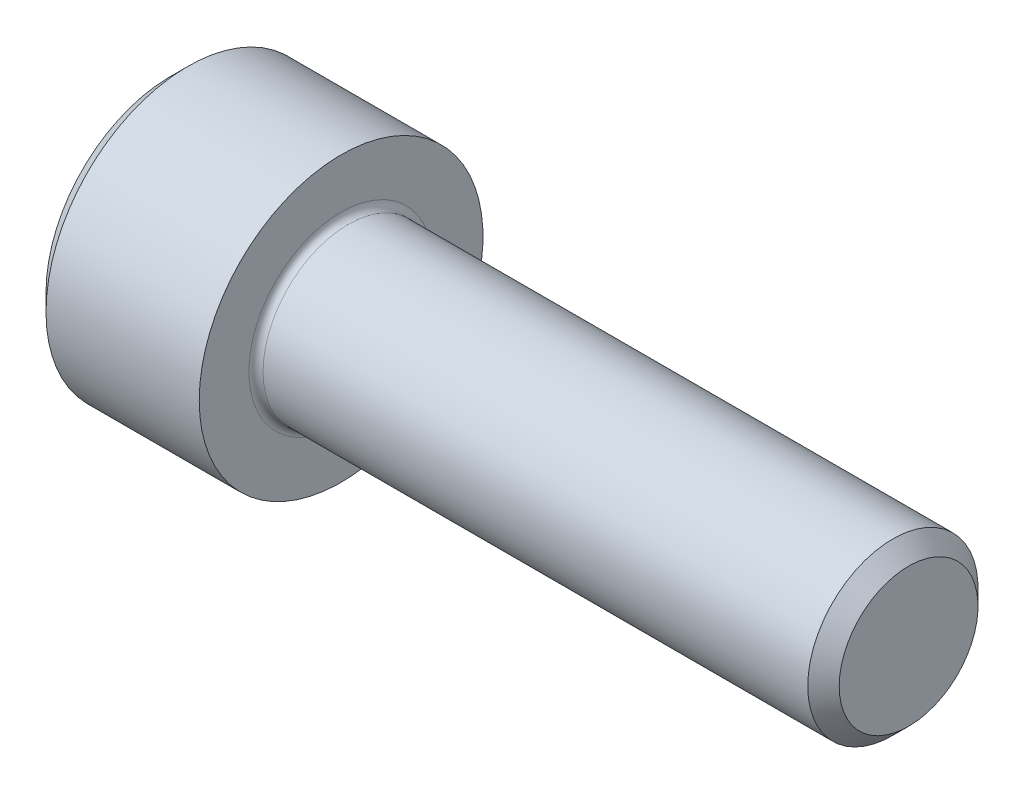
SolidWorks part; units mm, degrees
ref_plane "Plane1" through (0, 0, 0) normal (0, 0, 1) x (1, 0, 0)
ref_plane "Plane2" through (0, 0, 0) normal (0, 1, 0) x (1, 0, 0)
ref_plane "Plane3" through (0, 0, 0) normal (1, 0, 0) x (0, 0, -1)
sketch "BodySke" plane through (0, 0, 0) normal (0, 0, 1) x (1, 0, 0)
  line L0 (0, 0) -> (0, 4.4)
  line L1 (0.6, 5) -> (6, 5)
  line L2 (6, 5) -> (6, 3)
  line L3 (6, 3) -> (25.4455, 3)
  line L4 (26, 2.4455) -> (26, 0)
  line L5 (26, 0) -> (0, 0)
  line L6 (-31.75, 0) -> (127, 0) construction
  line L7 (0, 4.4) -> (0.6, 5)
  line L8 (26, 2.4455) -> (25.4455, 3)
  line L9 (0, -4.4) -> (0.6, -5) construction
  line L10 (26, -2.4455) -> (25.4455, -3) construction
  line L11 (7, 9.525) -> (7, 3.175) construction
  line L12 (6, 9.525) -> (6, 3.175) construction
  line L13 (-24, 9.525) -> (-24, 3.175) construction
  dimension "Diameter" = 6
  dimension "Head_ht" = 6
  dimension "Length" = 20
  dimension "Body_ch_ang" = 45
  dimension "Head_dia" = 10
  dimension "Head_ch_ang" = 45
  dimension "Minor_dia" = 4.891
  dimension "Advance" = 1
  dimension "Thread_nom" = 20
  dimension "Thread_length" = 50
  dimension "Head_ch_ht" = 0.6
revolve "Base-Revolve" add sketch "BodySke"
cosmetic thread "ThreadCosmetic" [suppressed]
fillet "Fillet1" radius 0.25 1 edges at (6, 0, 3)
sketch "Sketch2" plane through (0, 0, 0) normal (0, 0, 1) x (1, 0, 0)
  line L0 (0, 2.542) -> (3, 2.542)
  line L1 (3, 2.542) -> (4.4676, 0)
  line L2 (-31.75, 0) -> (127, 0) construction
  line L3 (4.4676, 0) -> (0, 0)
  line L4 (0, 0) -> (0, 2.542)
  line L5 (0, 4.4) -> (0, -4.4) construction
  line L6 (0, 0) -> (47.625, 0) construction
  line L7 (6, -5) -> (6, 5) construction
  dimension "D1" = 2.542
  dimension "D2" = 60
  dimension "Wall_thickness" = 3
revolve "Hex-PreBroach" cut sketch "Sketch2" angle 360 about L6
sketch "Sketch3" plane through (0, 0, 0) normal (-1, 0, 0) x (0, 0.5, 0.866)
  line L0 (1.4676, 2.542) -> (-1.4676, 2.542)
  line L1 (-1.4676, 2.542) -> (-2.9352, 0)
  line L2 (1.4676, 2.542) -> (2.9352, 0)
  line L3 (1.4676, -2.542) -> (2.9352, 0)
  line L4 (1.4676, -2.542) -> (-1.4676, -2.542)
  line L5 (-1.4676, -2.542) -> (-2.9352, 0)
  dimension "D1" = 2.542
  dimension "D2" = 2.542
  dimension "Hex_size" = 5.084
extrude "Hex" cut sketch "Sketch3" against normal blind 3
sketch "Sketch4" plane through (0, 0, 0) normal (-1, 0, 0) x (0, 0, 1)
  line L0 (0, 0) -> (2.8067, 0)
  line L1 (0, 0) -> (6.1484, 3.5498) construction
  line L2 (0, 0) -> (1.4033, 2.4307)
  line L3 (2.3336, 0.614) -> (2.6851, 0.817)
  line L4 (1.6986, 1.7139) -> (2.0501, 1.9169)
  arc A0 (2.3336, 0.614) -> (1.6986, 1.7139) centre (0, 0) ccw
  arc A1 (2.8067, 0) -> (2.6851, 0.817) centre (0, 0) ccw
  arc A2 (1.4033, 2.4307) -> (2.0501, 1.9169) centre (0, 0) cw
  dimension "D1" = 30
  dimension "Spline_n_dim" = 4.826
  dimension "Spline_m_dim" = 5.6134
  dimension "D2" = 60
  dimension "D3" = 0.635
  dimension "Spline_p_dim" = 1.27
extrude "Spline" [suppressed] cut sketch "Sketch4" against normal blind 3
pattern_circular "CirPattern1" [suppressed] count 6 every 60
sketch "Sketch5" plane through (0, 0, 0) normal (0, 0, 1) x (1, 0, 0)
  line L0 (-31.75, 0) -> (127, 0) construction
  line L2 (0, 4.4) -> (0, -4.4) construction
  circle A0 centre (2.3, 0) radius 0.675
  dimension "Drilled_hole_dia" = 1.35
  dimension "Drilled_hole_loc" = 2.3
extrude "Hole" [suppressed] cut sketch "Sketch5" against normal through all and the other way through all
pattern_circular "Drilled-4" [suppressed] count 2 every 60
pattern_circular "Drilled-6" [suppressed] count 3 every 60
sketch "ThdSchSke" plane through (0, 0, 0) normal (0, 0, 1) x (1, 0, 0)
  line L0 (7, -2.4455) -> (6.6117, -3)
  line L1 (7, -2.4455) -> (7.3883, -3)
  line L2 (7.3883, -3) -> (7.3883, -3.75)
  line L3 (-3.175, 0) -> (5.1513, 0) construction
  line L5 (7.3883, -3.75) -> (6.6117, -3.75)
  line L6 (6.6117, -3.75) -> (6.6117, -3)
  line L7 (0, 4.4) -> (0, -4.4) construction
  dimension "Thread_minor" = 4.891
  dimension "Diameter" = 6
  dimension "Start" = 7
  dimension "SideAngle" = 55
  dimension "VeeAngle" = 70
  dimension "Overcut" = 7.5
revolve "ThreadSchematic" [suppressed] cut sketch "ThdSchSke" angle 360 about L3
pattern_linear "ThdSchPat" [suppressed]
equation "\"D2@Sketch3\" = \"Hex_size@Sketch3\" / 2"
equation "\"D1@Sketch3\" = \"Hex_size@Sketch3\" / 2"
equation "\"D1@Sketch2\" = \"Hex_size@Sketch3\" / 2"
equation "\"D3@Sketch4\" = \"Spline_p_dim@Sketch4\" / 2"
equation "\"Thread_minor@ThreadCosmetic\"  =  \"Minor_dia@BodySke\""
equation "\"D2@CirPattern1\" = 360 / \"Num_teeth@CirPattern1\""
equation "\"Wall_thickness@Sketch2\" = \"Head_ht@BodySke\" - \"Key_eng@Hex\""
equation "\"Thread_length@ThreadCosmetic\" = ((sgn( (\"Length@BodySke\" - \"Advance@BodySke\" ) - \"Thread_nom@BodySke\" )-1)*( (\"Length@BodySke\" - \"Advance@BodySke\" ) - \"Thread_nom@BodySke\" ))/-2+ \"Thread_nom@BodySke\""
equation "\"Thread_minor@ThdSchSke\" = \"Minor_dia@BodySke\""
equation "\"Diameter@ThdSchSke\" = \"Diameter@BodySke\""
equation "\"Overcut@ThdSchSke\" = \"Diameter@BodySke\" * 1.25"
equation "\"Start@ThdSchSke\" = \"Head_ht@BodySke\" + \"Length@BodySke\" - \"Thread_length@ThreadCosmetic\"  '---Non-countersunk---"
equation "\"Num_threads@ThdSchPat\" = int( \"Thread_length@ThreadCosmetic\" / \"Advance@BodySke\" + 0.999 )  + 1"
equation "\"Advance@ThdSchPat\" = \"Thread_length@ThreadCosmetic\" /  (\"Num_threads@ThdSchPat\" - 1) 'relax it"
equation "\"Num_threads@ThdSchPat\" = \"Num_threads@ThdSchPat\" - sgn( \"Num_threads@ThdSchPat\" - 1) '---chamfered tips only---"
